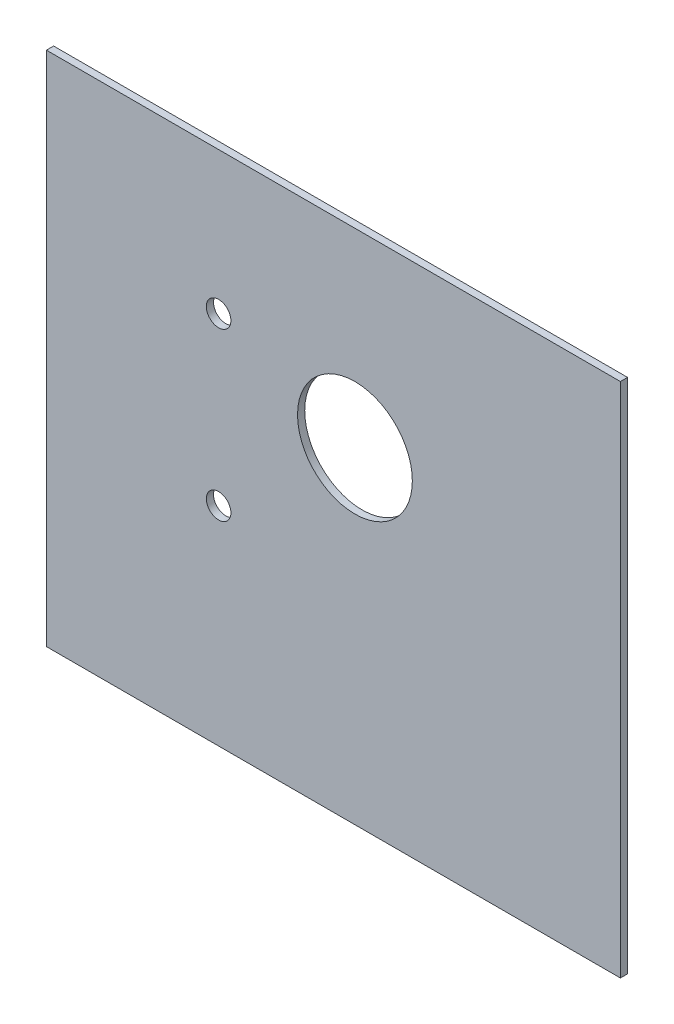
SolidWorks part; units mm, degrees
ref_plane "Plan de face" through (0, 0, 0) normal (0, 0, 1) x (1, 0, 0)
ref_plane "Plan de dessus" through (0, 0, 0) normal (0, 1, 0) x (1, 0, 0)
ref_plane "Plan de droite" through (0, 0, 0) normal (1, 0, 0) x (0, 0, -1)
sketch "Esquisse1" plane through (0, 0, 0) normal (0, 0, 1) x (1, 0, 0)
  line L1 (-200, 180) -> (200, 180)
  line L2 (-200, 180) -> (-200, -180)
  line L3 (-200, -180) -> (200, -180)
  line L4 (200, 180) -> (200, -180)
  line L5 (-200, 180) -> (200, -180) construction
  line L6 (-200, -180) -> (200, 180) construction
  point P0 (0, 0)
  dimension "D1" = 400
  dimension "D2" = 360
extrude "Boss.-Extru.1" add sketch "Esquisse1" along normal blind 5
sketch "Esquisse5" plane through (0, 0, 0) normal (0, 0, -1) x (-1, 0, 0)
  line L0 (-271.8045, 81) -> (240.3937, 81) construction
  line L1 (-200, 180) -> (200, 180) construction
  line L2 (200, 180) -> (200, -180) construction
  line L3 (-271.8045, -35) -> (271.8045, -35) construction
  line L4 (200, -180) -> (-200, -180) construction
  circle A0 centre (80, 81) radius 8.56
  circle A1 centre (80, -35) radius 8.56
  dimension "D2" = 17.12
  dimension "D5" = 17.12
  dimension "D1" = 99
  dimension "D3" = 120
  dimension "D4" = 145
  dimension "D6" = 120
extrude "Enlèv. mat.-Extru.3" cut sketch "Esquisse5" against normal blind 10
sketch "Esquisse6" plane through (0, 0, 0) normal (0, 0, -1) x (-1, 0, 0)
  line L0 (-200, -180) -> (-200, 180) construction
  line L1 (-200, 180) -> (200, 180) construction
  circle A0 centre (-15, 47.5) radius 40
  dimension "D3" = 80
  dimension "D1" = 185
  dimension "D2" = 132.5
extrude "Enlèv. mat.-Extru.4" cut sketch "Esquisse6" against normal blind 10
